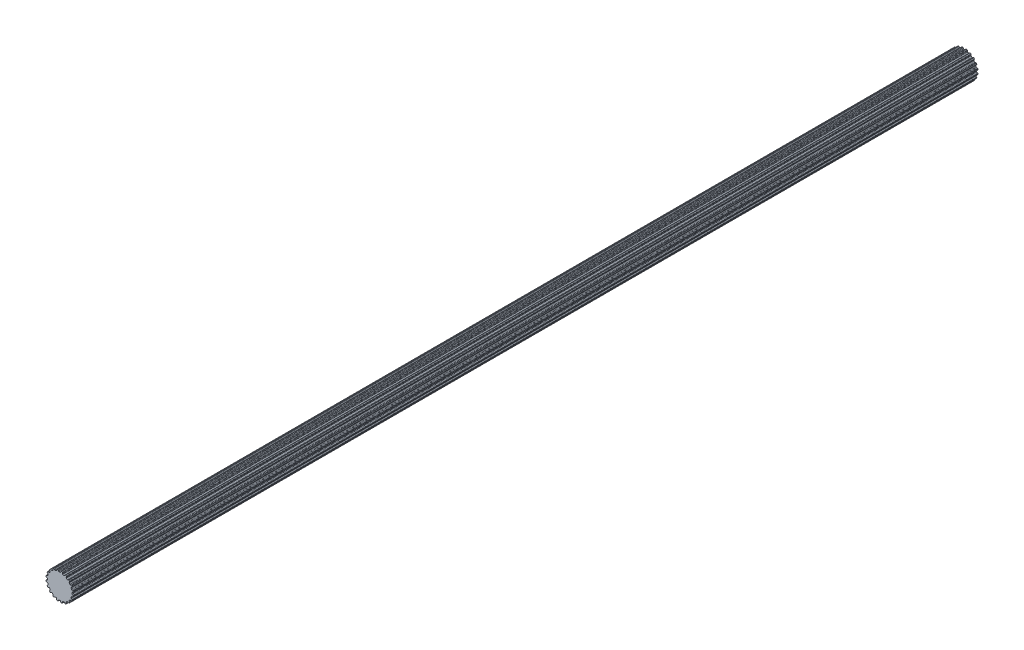
SolidWorks part; units mm, degrees
ref_plane "Front Plane" through (0, 0, 0) normal (0, 0, 1) x (1, 0, 0)
ref_plane "Top Plane" through (0, 0, 0) normal (0, 1, 0) x (1, 0, 0)
ref_plane "Right Plane" through (0, 0, 0) normal (1, 0, 0) x (0, 0, -1)
sketch "Sketch1" plane through (0, 0, 0) normal (0, 0, 1) x (1, 0, 0)
  line L0 (-0.1069, 2.9699) -> (0.1069, 2.9699)
  line L1 (0.3159, 3.2375) -> (0.2537, 3.0575)
  line L2 (-0.2964, 3.2367) -> (-0.2318, 3.0575)
  line L3 (-0.2964, 3.2367) -> (0.3159, 3.2375) construction
  line L4 (0, 3.3252) -> (0, 0) construction
  line L5 (-0.2318, 3.0575) -> (0.2537, 3.0575) construction
  line L6 (-0.4281, 3.3241) -> (0.4281, 3.3263) construction
  line L7 (0.7183, 3.1698) -> (0.7244, 2.9795)
  line L8 (0.816, 2.8576) -> (1.0195, 2.7915)
  line L9 (1.3009, 2.9815) -> (1.1862, 2.8295)
  line L10 (1.6627, 2.7927) -> (1.6097, 2.6099)
  line L11 (1.6591, 2.4655) -> (1.8322, 2.3398)
  line L12 (2.1585, 2.4335) -> (2.0025, 2.3245)
  line L13 (2.4443, 2.1423) -> (2.3374, 1.9847)
  line L14 (2.3398, 1.8322) -> (2.4655, 1.6591)
  line L15 (2.8049, 1.6474) -> (2.6228, 1.5919)
  line L16 (2.9866, 1.2821) -> (2.8363, 1.1653)
  line L17 (2.7915, 1.0195) -> (2.8576, 0.816)
  line L18 (3.1767, 0.7) -> (2.9863, 0.7035)
  line L19 (3.2367, 0.2964) -> (3.0575, 0.2318)
  line L20 (2.9699, 0.1069) -> (2.9699, -0.1069)
  line L21 (3.2375, -0.3159) -> (3.0575, -0.2537)
  line L22 (3.1698, -0.7183) -> (2.9795, -0.7244)
  line L23 (2.8576, -0.816) -> (2.7915, -1.0195)
  line L24 (2.9815, -1.3009) -> (2.8295, -1.1862)
  line L25 (2.7927, -1.6627) -> (2.6099, -1.6097)
  line L26 (2.4655, -1.6591) -> (2.3398, -1.8322)
  line L27 (2.4335, -2.1585) -> (2.3245, -2.0025)
  line L28 (2.1423, -2.4443) -> (1.9847, -2.3374)
  line L29 (1.8322, -2.3398) -> (1.6591, -2.4655)
  line L30 (1.6474, -2.8049) -> (1.5919, -2.6228)
  line L31 (1.2821, -2.9866) -> (1.1653, -2.8363)
  line L32 (1.0195, -2.7915) -> (0.816, -2.8576)
  line L33 (0.7, -3.1767) -> (0.7035, -2.9863)
  line L34 (0.2964, -3.2367) -> (0.2318, -3.0575)
  line L35 (0.1069, -2.9699) -> (-0.1069, -2.9699)
  line L36 (-0.3159, -3.2375) -> (-0.2537, -3.0575)
  line L37 (-0.7183, -3.1698) -> (-0.7244, -2.9795)
  line L38 (-0.816, -2.8576) -> (-1.0195, -2.7915)
  line L39 (-1.3009, -2.9815) -> (-1.1862, -2.8295)
  line L40 (-1.6627, -2.7927) -> (-1.6097, -2.6099)
  line L41 (-1.6591, -2.4655) -> (-1.8322, -2.3398)
  line L42 (-2.1585, -2.4335) -> (-2.0025, -2.3245)
  line L43 (-2.4443, -2.1423) -> (-2.3374, -1.9847)
  line L44 (-2.3398, -1.8322) -> (-2.4655, -1.6591)
  line L45 (-2.8049, -1.6474) -> (-2.6228, -1.5919)
  line L46 (-2.9866, -1.2821) -> (-2.8363, -1.1653)
  line L47 (-2.7915, -1.0195) -> (-2.8576, -0.816)
  line L48 (-3.1767, -0.7) -> (-2.9863, -0.7035)
  line L49 (-3.2367, -0.2964) -> (-3.0575, -0.2318)
  line L50 (-2.9699, -0.1069) -> (-2.9699, 0.1069)
  line L51 (-3.2375, 0.3159) -> (-3.0575, 0.2537)
  line L52 (-3.1698, 0.7183) -> (-2.9795, 0.7244)
  line L53 (-2.8576, 0.816) -> (-2.7915, 1.0195)
  line L54 (-2.9815, 1.3009) -> (-2.8295, 1.1862)
  line L55 (-2.7927, 1.6627) -> (-2.6099, 1.6097)
  line L56 (-2.4655, 1.6591) -> (-2.3398, 1.8322)
  line L57 (-2.4335, 2.1585) -> (-2.3245, 2.0025)
  line L58 (-2.1423, 2.4443) -> (-1.9847, 2.3374)
  line L59 (-1.8322, 2.3398) -> (-1.6591, 2.4655)
  line L60 (-1.6474, 2.8049) -> (-1.5919, 2.6228)
  line L61 (-1.2821, 2.9866) -> (-1.1653, 2.8363)
  line L62 (-1.0195, 2.7915) -> (-0.816, 2.8576)
  line L63 (-0.7, 3.1767) -> (-0.7035, 2.9863)
  line L64 (0.4281, 3.3263) -> (0.62, 3.2938)
  line L65 (1.4351, 3.0312) -> (1.6075, 2.9409)
  line L66 (2.3015, 2.4394) -> (2.4376, 2.3003)
  line L67 (2.9427, 1.6088) -> (3.0291, 1.4344)
  line L68 (3.2958, 0.6207) -> (3.3241, 0.4281)
  line L69 (3.3263, -0.4281) -> (3.2938, -0.62)
  line L70 (3.0312, -1.4351) -> (2.9409, -1.6075)
  line L71 (2.4394, -2.3015) -> (2.3003, -2.4376)
  line L72 (1.6088, -2.9427) -> (1.4344, -3.0291)
  line L73 (0.6207, -3.2958) -> (0.4281, -3.3241)
  line L74 (-0.4281, -3.3263) -> (-0.62, -3.2938)
  line L75 (-1.4351, -3.0312) -> (-1.6075, -2.9409)
  line L76 (-2.3015, -2.4394) -> (-2.4376, -2.3003)
  line L77 (-2.9427, -1.6088) -> (-3.0291, -1.4344)
  line L78 (-3.2958, -0.6207) -> (-3.3241, -0.4281)
  line L79 (-3.3263, 0.4281) -> (-3.2938, 0.62)
  line L80 (-3.0312, 1.4351) -> (-2.9409, 1.6075)
  line L81 (-2.4394, 2.3015) -> (-2.3003, 2.4376)
  line L82 (-1.6088, 2.9427) -> (-1.4344, 3.0291)
  line L83 (-0.6207, 3.2958) -> (-0.4281, 3.3241)
  arc A0 (0.2537, 3.0575) -> (0.1069, 2.9699) centre (0.1283, 3.1009) cw
  arc A1 (-0.2318, 3.0575) -> (-0.1069, 2.9699) centre (-0.1069, 3.1026) ccw
  arc A2 (0.62, 3.2938) -> (0.7183, 3.1698) centre (0.5856, 3.1656) cw
  arc A3 (0.7244, 2.9795) -> (0.816, 2.8576) centre (0.857, 2.9838) ccw
  arc A4 (-0.4281, 3.3241) -> (-0.2964, 3.2367) centre (-0.4213, 3.1916) cw
  arc A5 (0.4281, 3.3263) -> (0.3159, 3.2375) centre (0.4413, 3.1942) ccw
  arc A6 (1.1862, 2.8295) -> (1.0195, 2.7915) centre (1.0802, 2.9095) cw
  arc A7 (1.4351, 3.0312) -> (1.3009, 2.9815) centre (1.4068, 2.9015) ccw
  arc A8 (1.6075, 2.9409) -> (1.6627, 2.7927) centre (1.5352, 2.8297) cw
  arc A9 (1.6097, 2.6099) -> (1.6591, 2.4655) centre (1.7371, 2.5729) ccw
  arc A10 (2.0025, 2.3245) -> (1.8322, 2.3398) centre (1.9264, 2.4332) cw
  arc A11 (2.3015, 2.4394) -> (2.1585, 2.4335) centre (2.2346, 2.3248) ccw
  arc A12 (2.4376, 2.3003) -> (2.4443, 2.1423) centre (2.3345, 2.2168) cw
  arc A13 (2.3374, 1.9847) -> (2.3398, 1.8322) centre (2.4472, 1.9102) ccw
  arc A14 (2.6228, 1.5919) -> (2.4655, 1.6591) centre (2.5841, 1.7189) cw
  arc A15 (2.9427, 1.6088) -> (2.8049, 1.6474) centre (2.8436, 1.5205) ccw
  arc A16 (3.0291, 1.4344) -> (2.9866, 1.2821) centre (2.9052, 1.3869) cw
  arc A17 (2.8363, 1.1653) -> (2.7915, 1.0195) centre (2.9177, 1.0605) ccw
  arc A18 (2.9863, 0.7035) -> (2.8576, 0.816) centre (2.9887, 0.8362) cw
  arc A19 (3.2958, 0.6207) -> (3.1767, 0.7) centre (3.1743, 0.5673) ccw
  arc A20 (3.3241, 0.4281) -> (3.2367, 0.2964) centre (3.1916, 0.4213) cw
  arc A21 (3.0575, 0.2318) -> (2.9699, 0.1069) centre (3.1026, 0.1069) ccw
  arc A22 (3.0575, -0.2537) -> (2.9699, -0.1069) centre (3.1009, -0.1283) cw
  arc A23 (3.3263, -0.4281) -> (3.2375, -0.3159) centre (3.1942, -0.4413) ccw
  arc A24 (3.2938, -0.62) -> (3.1698, -0.7183) centre (3.1656, -0.5856) cw
  arc A25 (2.9795, -0.7244) -> (2.8576, -0.816) centre (2.9838, -0.857) ccw
  arc A26 (2.8295, -1.1862) -> (2.7915, -1.0195) centre (2.9095, -1.0802) cw
  arc A27 (3.0312, -1.4351) -> (2.9815, -1.3009) centre (2.9015, -1.4068) ccw
  arc A28 (2.9409, -1.6075) -> (2.7927, -1.6627) centre (2.8297, -1.5352) cw
  arc A29 (2.6099, -1.6097) -> (2.4655, -1.6591) centre (2.5729, -1.7371) ccw
  arc A30 (2.3245, -2.0025) -> (2.3398, -1.8322) centre (2.4332, -1.9264) cw
  arc A31 (2.4394, -2.3015) -> (2.4335, -2.1585) centre (2.3248, -2.2346) ccw
  arc A32 (2.3003, -2.4376) -> (2.1423, -2.4443) centre (2.2168, -2.3345) cw
  arc A33 (1.9847, -2.3374) -> (1.8322, -2.3398) centre (1.9102, -2.4472) ccw
  arc A34 (1.5919, -2.6228) -> (1.6591, -2.4655) centre (1.7189, -2.5841) cw
  arc A35 (1.6088, -2.9427) -> (1.6474, -2.8049) centre (1.5205, -2.8436) ccw
  arc A36 (1.4344, -3.0291) -> (1.2821, -2.9866) centre (1.3869, -2.9052) cw
  arc A37 (1.1653, -2.8363) -> (1.0195, -2.7915) centre (1.0605, -2.9177) ccw
  arc A38 (0.7035, -2.9863) -> (0.816, -2.8576) centre (0.8362, -2.9887) cw
  arc A39 (0.6207, -3.2958) -> (0.7, -3.1767) centre (0.5673, -3.1743) ccw
  arc A40 (0.4281, -3.3241) -> (0.2964, -3.2367) centre (0.4213, -3.1916) cw
  arc A41 (0.2318, -3.0575) -> (0.1069, -2.9699) centre (0.1069, -3.1026) ccw
  arc A42 (-0.2537, -3.0575) -> (-0.1069, -2.9699) centre (-0.1283, -3.1009) cw
  arc A43 (-0.4281, -3.3263) -> (-0.3159, -3.2375) centre (-0.4413, -3.1942) ccw
  arc A44 (-0.62, -3.2938) -> (-0.7183, -3.1698) centre (-0.5856, -3.1656) cw
  arc A45 (-0.7244, -2.9795) -> (-0.816, -2.8576) centre (-0.857, -2.9838) ccw
  arc A46 (-1.1862, -2.8295) -> (-1.0195, -2.7915) centre (-1.0802, -2.9095) cw
  arc A47 (-1.4351, -3.0312) -> (-1.3009, -2.9815) centre (-1.4068, -2.9015) ccw
  arc A48 (-1.6075, -2.9409) -> (-1.6627, -2.7927) centre (-1.5352, -2.8297) cw
  arc A49 (-1.6097, -2.6099) -> (-1.6591, -2.4655) centre (-1.7371, -2.5729) ccw
  arc A50 (-2.0025, -2.3245) -> (-1.8322, -2.3398) centre (-1.9264, -2.4332) cw
  arc A51 (-2.3015, -2.4394) -> (-2.1585, -2.4335) centre (-2.2346, -2.3248) ccw
  arc A52 (-2.4376, -2.3003) -> (-2.4443, -2.1423) centre (-2.3345, -2.2168) cw
  arc A53 (-2.3374, -1.9847) -> (-2.3398, -1.8322) centre (-2.4472, -1.9102) ccw
  arc A54 (-2.6228, -1.5919) -> (-2.4655, -1.6591) centre (-2.5841, -1.7189) cw
  arc A55 (-2.9427, -1.6088) -> (-2.8049, -1.6474) centre (-2.8436, -1.5205) ccw
  arc A56 (-3.0291, -1.4344) -> (-2.9866, -1.2821) centre (-2.9052, -1.3869) cw
  arc A57 (-2.8363, -1.1653) -> (-2.7915, -1.0195) centre (-2.9177, -1.0605) ccw
  arc A58 (-2.9863, -0.7035) -> (-2.8576, -0.816) centre (-2.9887, -0.8362) cw
  arc A59 (-3.2958, -0.6207) -> (-3.1767, -0.7) centre (-3.1743, -0.5673) ccw
  arc A60 (-3.3241, -0.4281) -> (-3.2367, -0.2964) centre (-3.1916, -0.4213) cw
  arc A61 (-3.0575, -0.2318) -> (-2.9699, -0.1069) centre (-3.1026, -0.1069) ccw
  arc A62 (-3.0575, 0.2537) -> (-2.9699, 0.1069) centre (-3.1009, 0.1283) cw
  arc A63 (-3.3263, 0.4281) -> (-3.2375, 0.3159) centre (-3.1942, 0.4413) ccw
  arc A64 (-3.2938, 0.62) -> (-3.1698, 0.7183) centre (-3.1656, 0.5856) cw
  arc A65 (-2.9795, 0.7244) -> (-2.8576, 0.816) centre (-2.9838, 0.857) ccw
  arc A66 (-2.8295, 1.1862) -> (-2.7915, 1.0195) centre (-2.9095, 1.0802) cw
  arc A67 (-3.0312, 1.4351) -> (-2.9815, 1.3009) centre (-2.9015, 1.4068) ccw
  arc A68 (-2.9409, 1.6075) -> (-2.7927, 1.6627) centre (-2.8297, 1.5352) cw
  arc A69 (-2.6099, 1.6097) -> (-2.4655, 1.6591) centre (-2.5729, 1.7371) ccw
  arc A70 (-2.3245, 2.0025) -> (-2.3398, 1.8322) centre (-2.4332, 1.9264) cw
  arc A71 (-2.4394, 2.3015) -> (-2.4335, 2.1585) centre (-2.3248, 2.2346) ccw
  arc A72 (-2.3003, 2.4376) -> (-2.1423, 2.4443) centre (-2.2168, 2.3345) cw
  arc A73 (-1.9847, 2.3374) -> (-1.8322, 2.3398) centre (-1.9102, 2.4472) ccw
  arc A74 (-1.5919, 2.6228) -> (-1.6591, 2.4655) centre (-1.7189, 2.5841) cw
  arc A75 (-1.6088, 2.9427) -> (-1.6474, 2.8049) centre (-1.5205, 2.8436) ccw
  arc A76 (-1.4344, 3.0291) -> (-1.2821, 2.9866) centre (-1.3869, 2.9052) cw
  arc A77 (-1.1653, 2.8363) -> (-1.0195, 2.7915) centre (-1.0605, 2.9177) ccw
  arc A78 (-0.7035, 2.9863) -> (-0.816, 2.8576) centre (-0.8362, 2.9887) cw
  arc A79 (-0.6207, 3.2958) -> (-0.7, 3.1767) centre (-0.5673, 3.1743) ccw
  point P14 (0, 2.9699)
  point P247 (0, 0)
  dimension "D4" = 0.1327
  dimension "D8" = 20
  dimension "D1" = 2.9699
  dimension "D2" = 0.2139
  dimension "D3" = 0.1904
  dimension "D5" = 0.0877
  dimension "D6" = 0.4855
  dimension "D7" = 0.8563
extrude "Boss-Extrude1" add sketch "Sketch1" along normal mid plane 220.726
sketch "Sketch2" plane through (0, 0, 110.363) normal (0, 0, 1) x (1, 0, 0)
  circle A0 centre (0, 0) radius 3.3516 construction
sketch "Sketch3" plane through (0, 0, -110.363) normal (0, 0, -1) x (-1, 0, 0)
  circle A0 centre (0, 0) radius 3.3516 construction
  circle A1 centre (0, 0) radius 3.3516 construction
